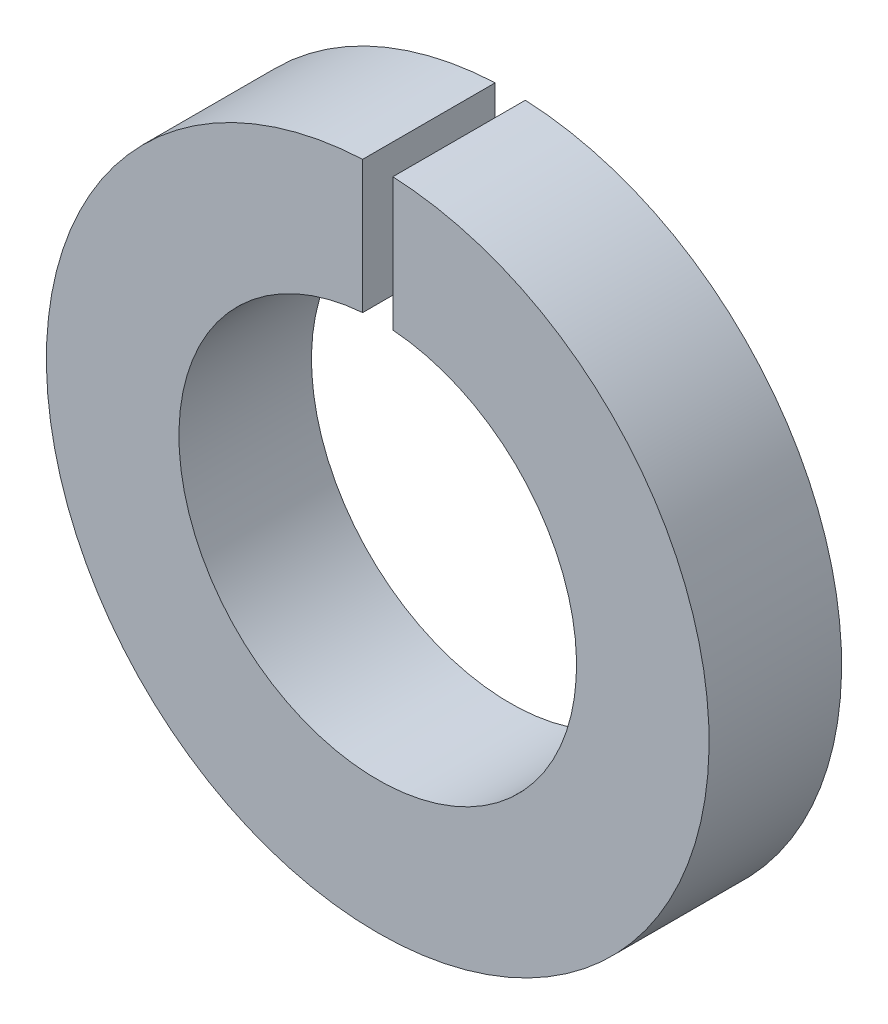
SolidWorks part; units mm, degrees
material "AISI 304"
ref_plane "Front Plane" through (0, 0, 0) normal (0, 0, 1) x (1, 0, 0)
ref_plane "Top Plane" through (0, 0, 0) normal (0, 1, 0) x (1, 0, 0)
ref_plane "Right Plane" through (0, 0, 0) normal (1, 0, 0) x (0, 0, -1)
other "Configuration Table"
sketch "Sketch1" plane through (0, 0, 0) normal (0, 0, 1) x (1, 0, 0)
  line L0 (0, 1.05) -> (0, 1.75) construction
  circle A0 centre (0, 0) radius 1.05
  circle A1 centre (0, 0) radius 1.75
  dimension "D1" = 2.1
  dimension "D2" = 0.7
extrude "Boss-Extrude1" add sketch "Sketch1" along normal blind 0.7
sketch "Sketch2" plane through (0, 0, 0.7) normal (0, 0, 1) x (1, 0, 0)
  line L0 (-0.0796, 1.047) -> (-0.0796, 1.7482)
  line L1 (0.0796, 1.7482) -> (0.0796, 1.047)
  circle A0 centre (0, 0) radius 1.05 construction
  circle A1 centre (0, 0) radius 1.75 construction
  circle A3 centre (0, 0) radius 1.75
  circle A4 centre (0, 0) radius 1.75
  circle M2 centre (0, 0) radius 1.75
  circle M3 centre (0, 0) radius 1.05
  dimension "D1" = 0
extrude "Cut-Extrude1" cut sketch "Sketch2" against normal blind 1 contours L1 L0 M2 M3
